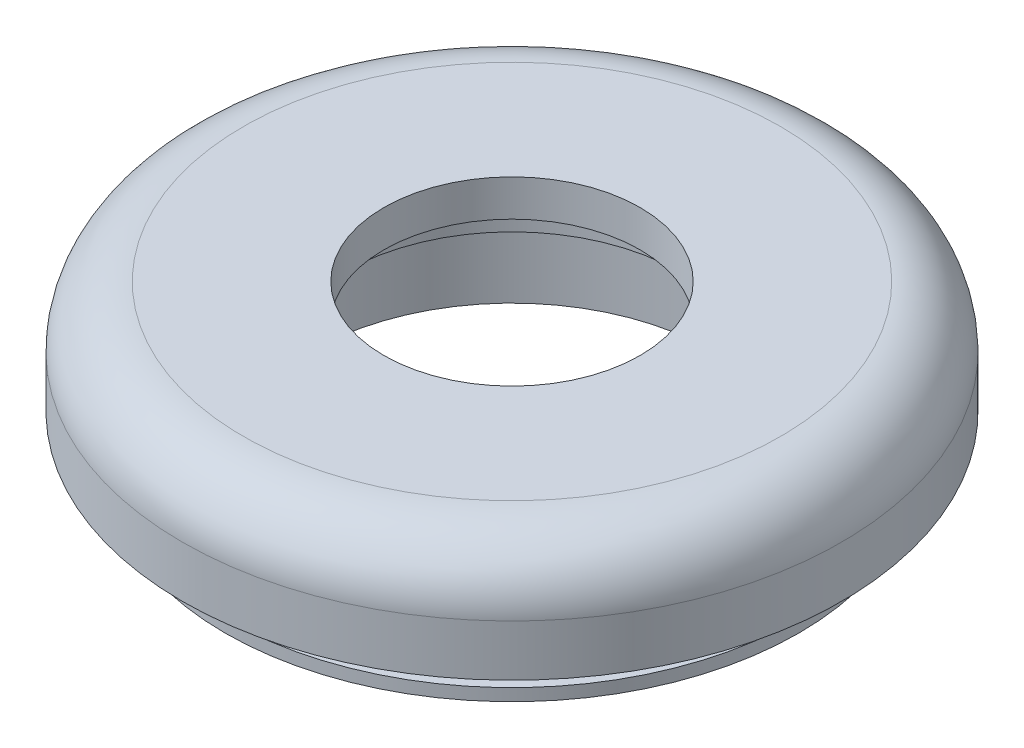
SolidWorks part; units mm, degrees
ref_plane "前视基准面" through (0, 0, 0) normal (0, 0, 1) x (1, 0, 0)
ref_plane "上视基准面" through (0, 0, 0) normal (0, 1, 0) x (1, 0, 0)
ref_plane "右视基准面" through (0, 0, 0) normal (1, 0, 0) x (0, 0, -1)
sketch "草图1" plane through (0, 0, 0) normal (0, 0, 1) x (1, 0, 0)
  line L0 (0, 0) -> (0, 62.7965)
sketch "草图2" plane through (0, 0, 0) normal (0, 0, 1) x (1, 0, 0)
  line L0 (0, 0) -> (-13.75, 0) construction
  line L1 (-13.75, 0) -> (-13.75, 3.2)
  line L5 (-10.5, 3.2) -> (-13.75, 3.2)
  line L10 (-27, 6.2) -> (-10.5, 6.2)
  line L18 (-13.75, 0) -> (-16.5, 0)
  line L30 (-10.5, 6.2) -> (-10.5, 3.2)
  line L31 (-20.9, -3) -> (-20.9, -6)
  line L32 (-20.9, -6) -> (-23.5, -6)
  line L40 (-23.5, -6) -> (-23.5, -7)
  line L41 (-23.5, -7) -> (-16.5, -7)
  line L42 (-16.5, 0) -> (-16.5, -7)
  line L43 (-20.9, -3) -> (-27, -3)
  line L44 (-27, -3) -> (-27, 6.2)
  point P5 (0, 0)
revolve "旋转1" add sketch "草图2" angle 360 about L0
fillet "圆角1" radius 5 1 edges at (0, 6.2, -27)
